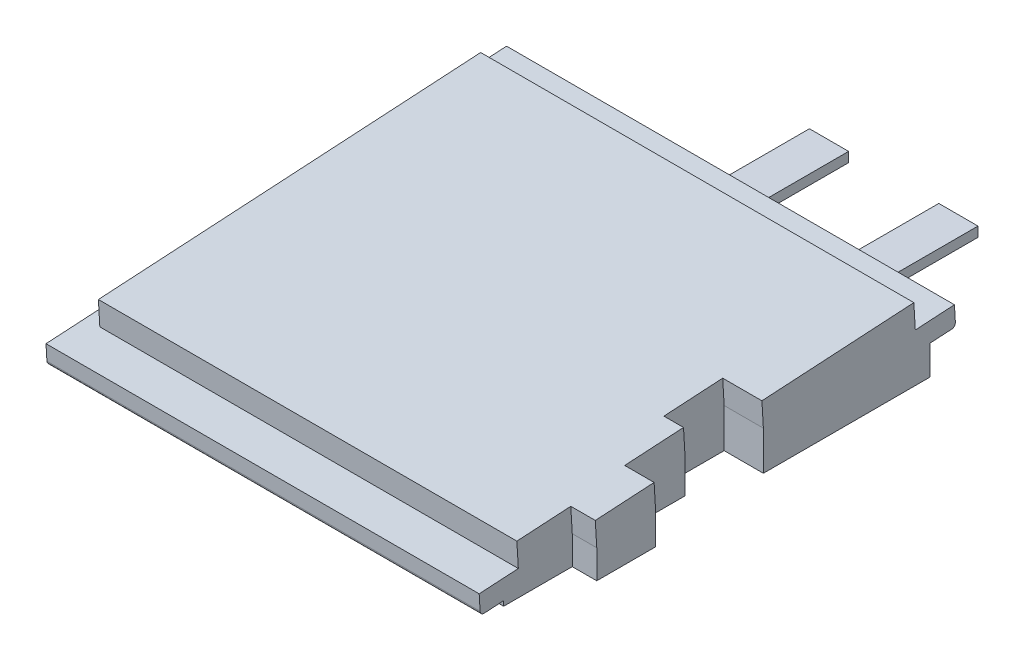
SolidWorks part; units mm, degrees
ref_plane "Front Plane" through (0, 0, 0) normal (0, 0, 1) x (1, 0, 0)
ref_plane "Top Plane" through (0, 0, 0) normal (0, 1, 0) x (1, 0, 0)
ref_plane "Right Plane" through (0, 0, 0) normal (1, 0, 0) x (0, 0, -1)
sketch "Sketch1" plane through (0, 0, 0) normal (0, 1, 0) x (1, 0, 0)
  line L0 (0, 0) -> (137.16, 0)
  line L1 (0, 0) -> (0, -133.35)
  line L2 (137.16, 0) -> (137.16, -53.975)
  line L3 (137.16, -53.975) -> (124.46, -53.975)
  line L4 (124.46, -53.975) -> (124.46, -73.025)
  line L5 (130.81, -73.025) -> (130.81, -92.075)
  line L6 (124.46, -73.025) -> (130.81, -73.025)
  line L7 (130.81, -92.075) -> (140.335, -92.075)
  line L8 (140.335, -92.075) -> (140.335, -111.125)
  line L9 (140.335, -111.125) -> (132.3975, -111.125)
  line L10 (132.3975, -111.125) -> (132.3975, -133.35)
  line L11 (0, -133.35) -> (132.3975, -133.35)
  dimension "D1" = 137.16
  dimension "D2" = 133.35
  dimension "D3" = 53.975
  dimension "D4" = 12.7
  dimension "D5" = 19.05
  dimension "D6" = 6.35
  dimension "D7" = 19.05
  dimension "D8" = 9.525
  dimension "D9" = 19.05
  dimension "D10" = 7.9375
extrude "Boss-Extrude1" add sketch "Sketch1" along normal blind 15.875
sketch "Sketch2" plane through (0, 0, 0) normal (-1, 0, 0) x (0, 0, 1)
  line L0 (133.35, 7.9375) -> (133.35, 15.875)
  line L1 (133.35, 15.875) -> (133.35, 0) construction
  line L2 (133.35, 15.875) -> (0, 15.875)
  line L3 (0, 15.875) -> (133.35, 7.9375)
  line L4 (0, 0) -> (133.35, 0) construction
  dimension "D1" = 7.9375
extrude "Cut-Extrude1" cut sketch "Sketch2" against normal through all
sketch "Sketch3" plane through (0, 15.819, 0.9416) normal (0, 0.9982, 0.0594) x (1, 0, 0)
  line L0 (0, 0.9433) -> (0, -132.6428) construction
  line L1 (-7.9375, 8.8808) -> (137.16, 8.8808)
  line L2 (-7.9375, 8.8808) -> (-7.9375, -140.5803)
  line L5 (137.16, 0.9433) -> (0, 0.9433) construction
  line L6 (-7.9375, -140.5803) -> (132.3975, -140.5803)
  line L7 (132.3975, -132.6428) -> (0, -132.6428) construction
  line L8 (132.3975, -110.3784) -> (132.3975, -132.6428) construction
  line L9 (132.3975, -140.5803) -> (132.3975, -124.7053)
  line L10 (132.3975, -124.7053) -> (7.9375, -124.7053)
  line L11 (7.9375, -124.7053) -> (7.9375, -6.9942)
  line L12 (7.9375, -6.9942) -> (137.16, -6.9942)
  line L13 (137.16, 0.9433) -> (137.16, -53.1273) construction
  line L14 (137.16, -6.9942) -> (137.16, 8.8808)
  dimension "D1" = 7.9375
  dimension "D2" = 7.9375
  dimension "D3" = 7.9375
  dimension "D4" = 0
  dimension "D5" = 7.9375
  dimension "D6" = 7.9375
  dimension "D7" = 7.9375
extrude "Boss-Extrude2" add sketch "Sketch3" against normal blind 6.35
fillet "Fillet1" radius 1.27 3 edges at (64.6113, 10.0079, -8.3008) (62.23, 1.1271, 140.8962) (-7.9375, 5.5675, 66.2977)
sketch "Sketch4" plane through (0, 15.819, 0.9416) normal (0, 0.9982, 0.0594) x (1, 0, 0)
  line L0 (-7.9375, 8.8808) -> (-7.9375, -140.5803) construction
  line L1 (-3.175, -3.8192) -> (103.8499, -3.8192)
  line L2 (-3.175, -3.8192) -> (-3.175, -127.8803)
  line L3 (-3.175, -127.8803) -> (132.3975, -127.8803)
  line L5 (-7.9375, -140.5803) -> (132.3975, -140.5803) construction
  line L6 (132.3975, -110.3784) -> (132.3975, -140.5803) construction
  line L7 (132.3975, -127.8803) -> (132.3975, -110.3784)
  line L8 (132.3975, -110.3784) -> (140.335, -110.3784)
  line L9 (140.335, -110.3784) -> (140.335, -91.2947)
  line L10 (140.335, -91.2947) -> (130.81, -91.2947)
  line L11 (130.81, -91.2947) -> (130.81, -72.211)
  line L12 (130.81, -72.211) -> (124.46, -72.211)
  line L13 (124.46, -72.211) -> (124.46, -53.1273)
  line L14 (124.46, -53.1273) -> (137.16, -53.1273)
  line L15 (137.16, -53.1273) -> (137.16, -3.8192)
  line L16 (137.16, 8.8808) -> (137.16, -53.1273) construction
  line L17 (137.16, -3.8192) -> (103.8499, -3.8192)
  line L18 (137.16, 8.8808) -> (-7.9375, 8.8808) construction
  dimension "D1" = 4.7625
  dimension "D2" = 12.7
  dimension "D3" = 0
  dimension "D4" = 12.7
  dimension "D5" = 17.5018
extrude "Boss-Extrude3" add sketch "Sketch4" along normal blind 7.9375
sketch "Sketch5" plane through (0, 0, 0) normal (0, 0, -1) x (-1, 0, 0)
  line L1 (-69.85, 9.2029) -> (-57.15, 9.2029)
  line L2 (-69.85, 9.2029) -> (-69.85, 6.0279)
  line L3 (-69.85, 6.0279) -> (-57.15, 6.0279)
  line L4 (-57.15, 9.2029) -> (-57.15, 6.0279)
  line L5 (-63.5, 6.0279) -> (-63.5, -5.0853) construction
  line L6 (0, 9.5138) -> (0, 0) construction
  line L7 (-105.41, 9.2029) -> (-105.41, -8.4766) construction
  line L8 (-111.76, 9.2029) -> (-99.06, 9.2029)
  line L9 (-111.76, 9.2029) -> (-111.76, 6.0279)
  line L10 (-111.76, 6.0279) -> (-99.06, 6.0279)
  line L11 (-99.06, 9.2029) -> (-99.06, 6.0279)
  line L12 (-137.16, 9.5138) -> (-137.16, 0) construction
  line L13 (-137.16, 16.3466) -> (7.9375, 16.3466) construction
  dimension "D1" = 63.5
  dimension "D2" = 31.75
  dimension "D3" = 12.7
  dimension "D4" = 3.175
  dimension "D5" = 3.175
  dimension "D6" = 12.7
  dimension "D7" = 7.1437
  dimension "D8" = 7.1437
extrude "Boss-Extrude4" add sketch "Sketch5" along normal blind 40.9575
